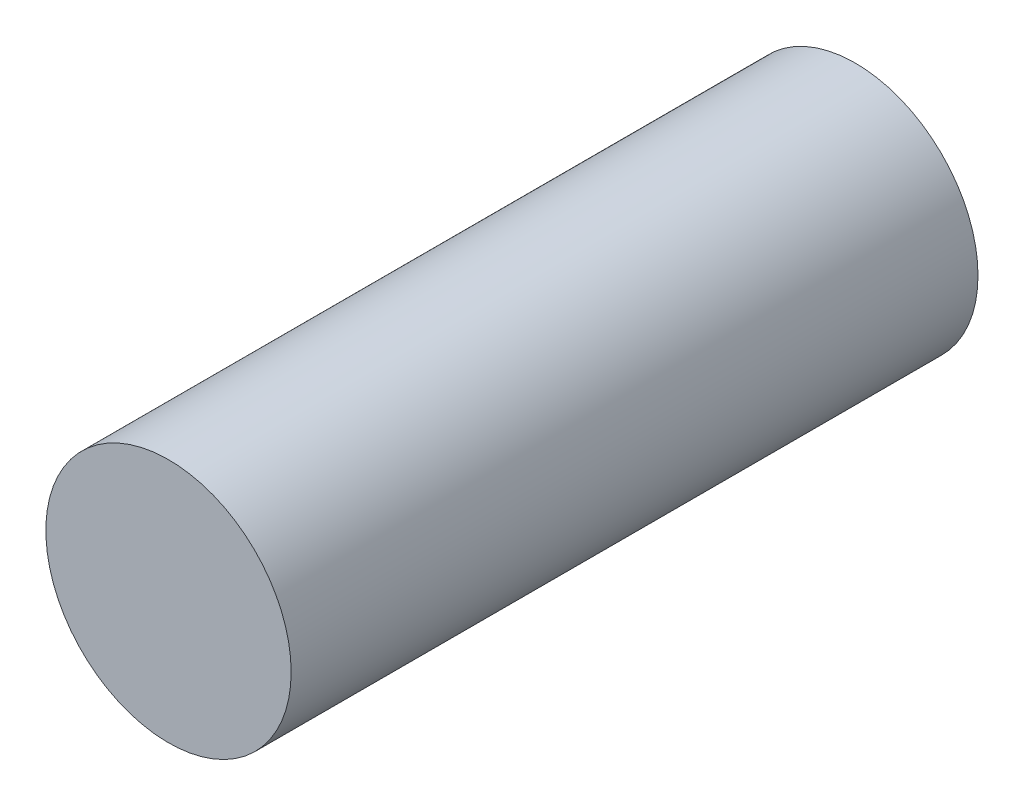
SolidWorks part; units mm, degrees
ref_plane "Спереди" through (0, 0, 0) normal (0, 0, 1) x (1, 0, 0)
ref_plane "Сверху" through (0, 0, 0) normal (0, 1, 0) x (1, 0, 0)
ref_plane "Справа" through (0, 0, 0) normal (1, 0, 0) x (0, 0, -1)
sketch "Эскиз1" plane through (0, 0, 0) normal (0, 0, 1) x (1, 0, 0)
  circle A2 centre (0, 0) radius 12.5
extrude "Бобышка-Вытянуть1" add sketch "Эскиз1" along normal blind 70
